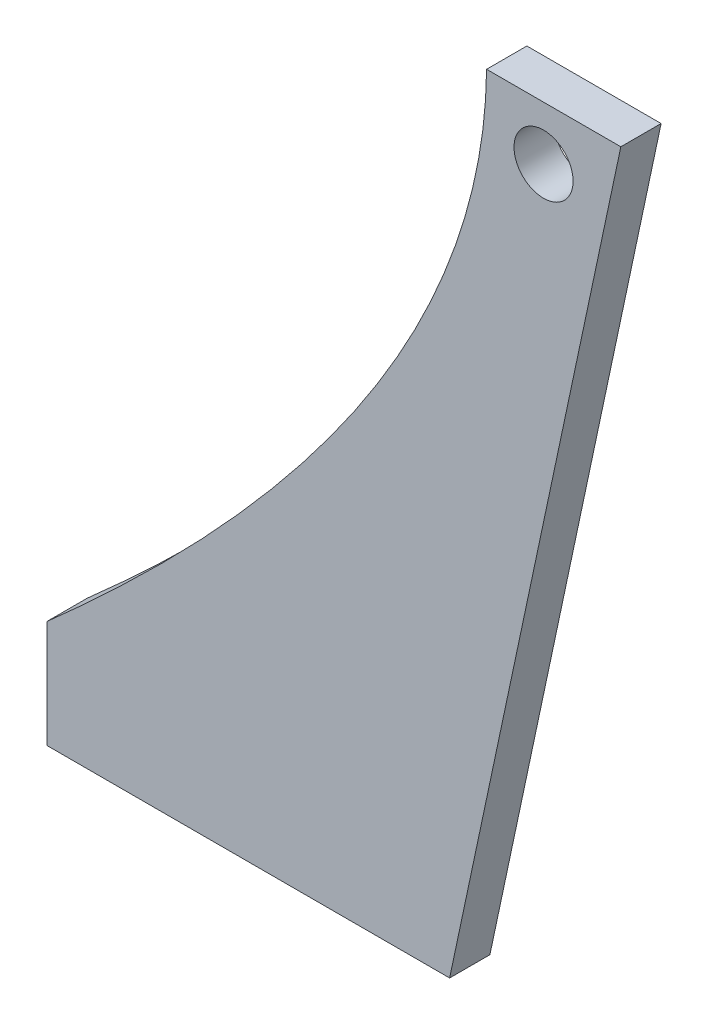
SolidWorks part; units mm, degrees
ref_plane "Front Plane" through (0, 0, 0) normal (0, 0, 1) x (1, 0, 0)
ref_plane "Top Plane" through (0, 0, 0) normal (0, 1, 0) x (1, 0, 0)
ref_plane "Right Plane" through (0, 0, 0) normal (1, 0, 0) x (0, 0, -1)
sketch "Sketch2" plane through (0, 0, 0) normal (0, 0, 1) x (1, 0, 0)
  line L0 (0, 0) -> (150, 0)
  line L1 (150, 0) -> (213.767, 300)
  line L2 (213.767, 300) -> (163.767, 300)
  line L5 (0, 40) -> (0, 0)
  spline S0 degree 2 poles (163.767, 300) (162.6604, 183.8285) (0, 40) knots 0 0 0 0.298725 0.298725 0.298725
  dimension "D1" = 150
  dimension "D2" = 40
  dimension "D3" = 300
  dimension "D4" = 78
  dimension "D5" = 50
extrude "Boss-Extrude1" add sketch "Sketch2" against normal blind 15
sketch "Sketch3" plane through (0, 0, 0) normal (0, 0, 1) x (1, 0, 0)
  line L0 (150, 0) -> (213.767, 300) construction
  line L1 (213.767, 300) -> (163.767, 300) construction
  circle A0 centre (184.9797, 280) radius 11
  dimension "D1" = 24
  dimension "D" = 22
  dimension "20" = 20
extrude "Cut-Extrude1" cut sketch "Sketch3" against normal through all
